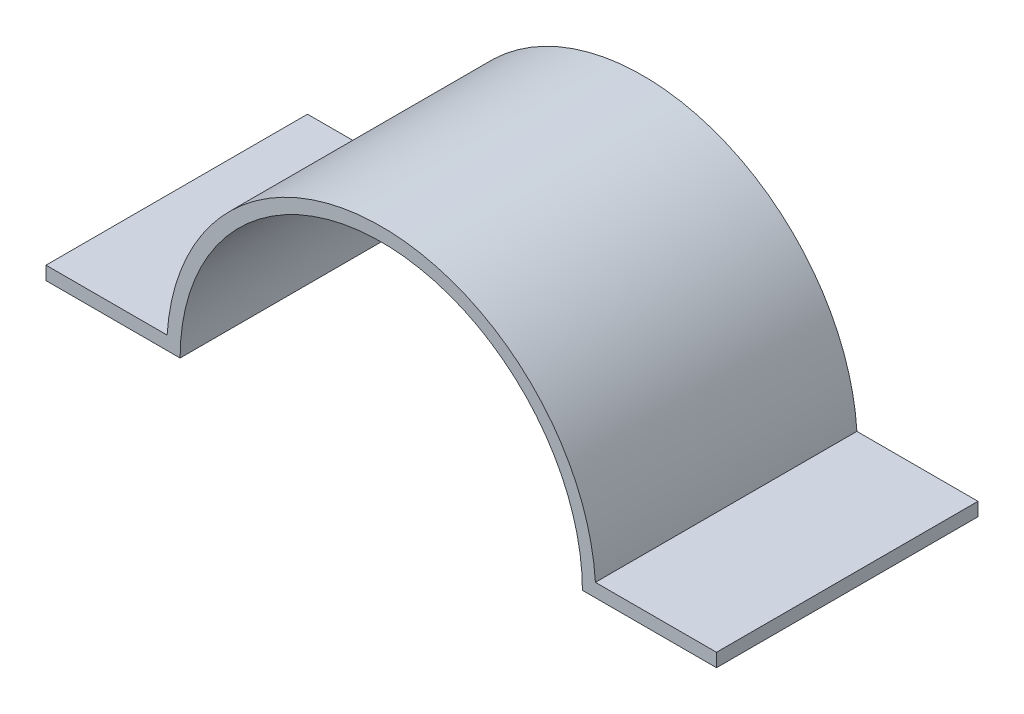
SolidWorks part; units mm, degrees
ref_plane "Front Plane" through (0, 0, 0) normal (0, 0, 1) x (1, 0, 0)
ref_plane "Top Plane" through (0, 0, 0) normal (0, 1, 0) x (1, 0, 0)
ref_plane "Right Plane" through (0, 0, 0) normal (1, 0, 0) x (0, 0, -1)
sketch "Sketch1" plane through (0, 0, 0) normal (0, 0, 1) x (1, 0, 0)
  line L0 (0, 0) -> (20, 0)
  line L1 (100, 0) -> (80, 0)
  arc A0 (20, 0) -> (80, 0) centre (50, 0) cw
  dimension "D2" = 30
  dimension "D1" = 20
  dimension "D3" = 20
extrude "Extrude-Thin2" add sketch "Sketch1" along normal blind 39 thin contours L0 A0 L1 thin type one direction wall 2
